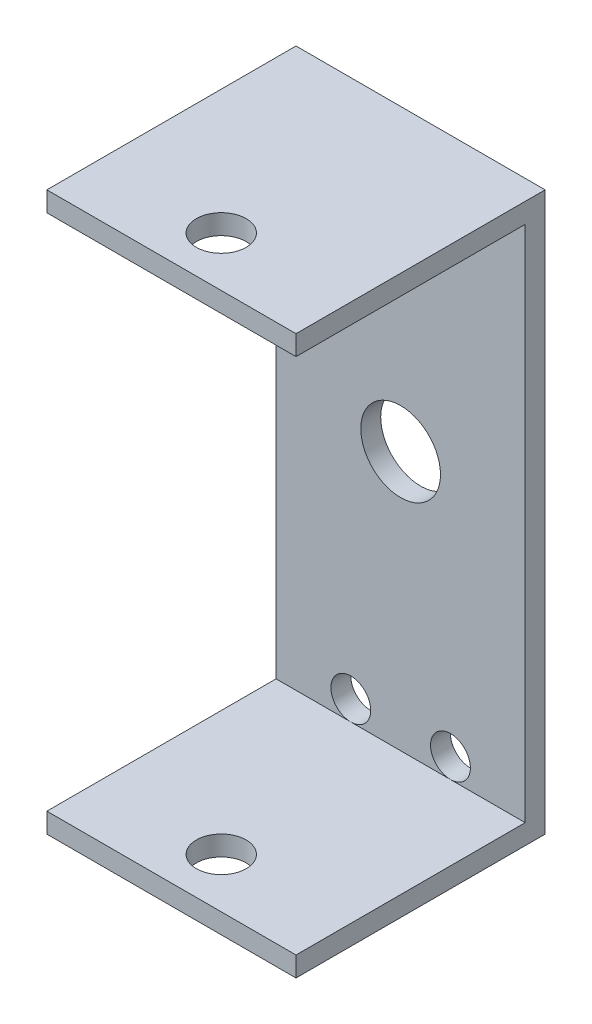
SolidWorks part; units mm, degrees
ref_plane "Front Plane" through (0, 0, 0) normal (0, 0, 1) x (1, 0, 0)
ref_plane "Top Plane" through (0, 0, 0) normal (0, 1, 0) x (1, 0, 0)
ref_plane "Right Plane" through (0, 0, 0) normal (1, 0, 0) x (0, 0, -1)
sketch "Sketch1" plane through (0, 0, 0) normal (0, 0, 1) x (1, 0, 0)
  line L1 (-12.6748, 30.5029) -> (12.3252, 30.5029)
  line L2 (-12.6748, 30.5029) -> (-12.6748, -21.4971)
  line L3 (-12.6748, -21.4971) -> (12.3252, -21.4971)
  line L4 (12.3252, 30.5029) -> (12.3252, -21.4971)
  dimension "D1" = 25
  dimension "D2" = 52
extrude "Boss-Extrude1" add sketch "Sketch1" along normal blind 2
sketch "Sketch2" plane through (0, 30.5029, 0) normal (0, 1, 0) x (1, 0, 0)
  line L1 (-12.6748, 0) -> (12.3252, 0)
  line L2 (-12.6748, 0) -> (-12.6748, -25)
  line L3 (-12.6748, -25) -> (12.3252, -25)
  line L4 (12.3252, 0) -> (12.3252, -25)
  dimension "D1" = 25
  dimension "D2" = 25
extrude "Boss-Extrude2" add sketch "Sketch2" along normal blind 2
sketch "Sketch3" plane through (0, -21.4971, 0) normal (0, -1, 0) x (-1, 0, 0)
  line L1 (-12.3252, 0) -> (12.6748, 0)
  line L2 (-12.3252, 0) -> (-12.3252, -25)
  line L3 (-12.3252, -25) -> (12.6748, -25)
  line L4 (12.6748, 0) -> (12.6748, -25)
  dimension "D1" = 25
  dimension "D2" = 25
extrude "Boss-Extrude3" add sketch "Sketch3" along normal blind 2
sketch "Sketch5" plane through (0, 0, 0) normal (0, 0, -1) x (-1, 0, 0)
  line L0 (12.6748, 32.5029) -> (12.6748, -23.4971) construction
  circle A0 centre (0.1748, 4.5029) radius 4
  dimension "D1" = 12.5
extrude "Cut-Extrude2" cut sketch "Sketch5" against normal blind 21
sketch "Sketch7" plane through (0, -23.4971, 0) normal (0, -1, 0) x (-1, 0, 0)
  line L0 (-12.3252, -25) -> (12.6748, -25) construction
  circle A0 centre (0.1748, -20) radius 2.5
  dimension "D1" = 5
extrude "Cut-Extrude4" cut sketch "Sketch7" against normal blind 84
sketch "Sketch8" plane through (0, 0, 0) normal (0, 0, -1) x (-1, 0, 0)
  line L0 (12.6748, 32.5029) -> (12.6748, -23.4971) construction
  line L2 (-12.3252, -21.4971) -> (-12.3252, 30.5029) construction
  line L3 (12.6748, -23.4971) -> (-12.3252, -23.4971) construction
  line L4 (-12.3252, 32.5029) -> (12.6748, 32.5029) construction
  circle A0 centre (5.1748, -19.4971) radius 2
  circle A1 centre (-4.8252, -19.4971) radius 2
  circle A2 centre (-4.8252, 28.5029) radius 2
  circle A3 centre (5.1748, 28.5029) radius 2
  point P8 (12.6748, 4.5029)
  point P11 (-12.3252, 4.5029)
  point P12 (12.6748, 4.5029)
  point P13 (-12.3252, 4.5029)
  point P16 (0.1748, -23.4971)
  point P19 (0.1748, -23.4971)
  point P20 (0.1748, 32.5029)
  point P23 (0.1748, 32.5029)
  dimension "D1" = 24
  dimension "D2" = 24
  dimension "D3" = 24
  dimension "D4" = 24
  dimension "D5" = 5
  dimension "D6" = 5
  dimension "D7" = 5
  dimension "D8" = 5
extrude "Cut-Extrude5" cut sketch "Sketch8" against normal blind 10
